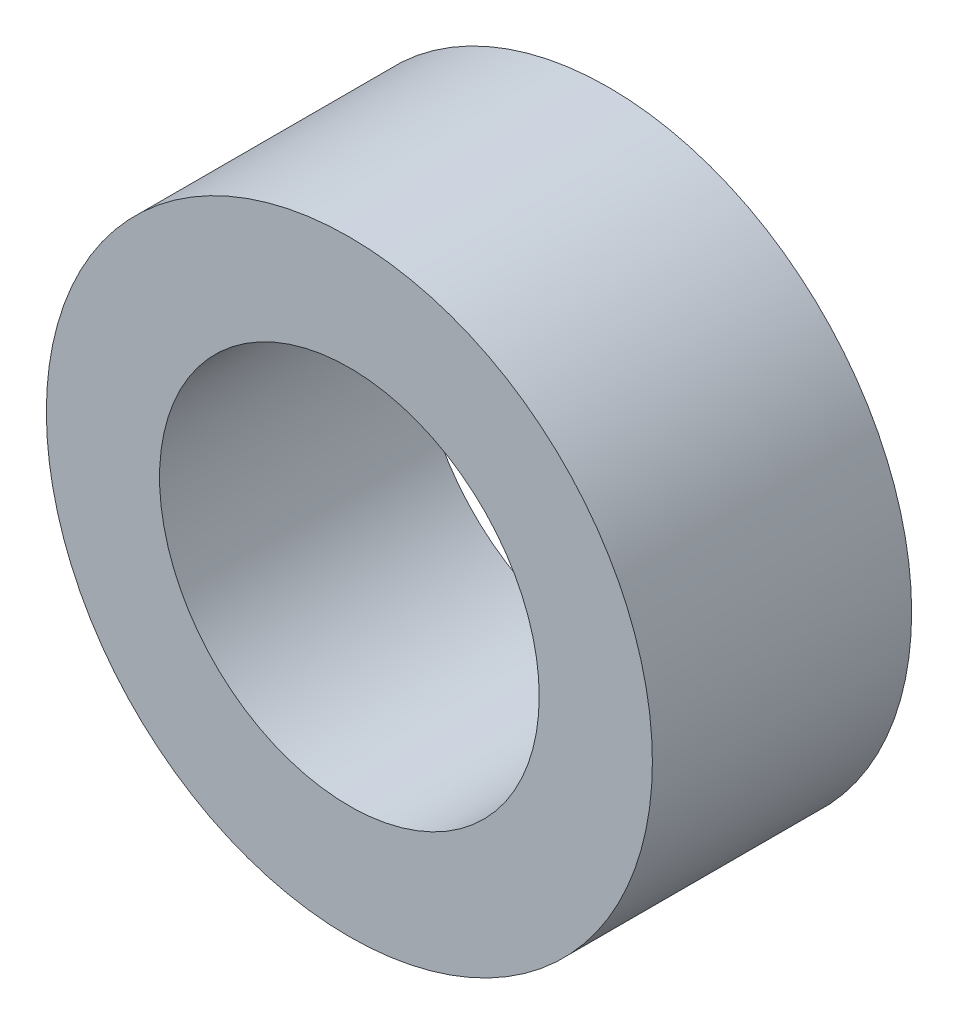
SolidWorks part; units mm, degrees
material "Силиконовая резина"
ref_plane "Спереди" through (0, 0, 0) normal (0, 0, 1) x (1, 0, 0)
ref_plane "Сверху" through (0, 0, 0) normal (0, 1, 0) x (1, 0, 0)
ref_plane "Справа" through (0, 0, 0) normal (1, 0, 0) x (0, 0, -1)
sketch "Эскиз1" plane through (0, 0, 0) normal (0, 0, 1) x (1, 0, 0)
  circle A0 centre (0, 0) radius 5.6384
  circle A1 centre (0, 0) radius 9
  dimension "D1" = 18
extrude "Бобышка-Вытянуть1" add sketch "Эскиз1" against normal up to surface (7.7 mm away)
